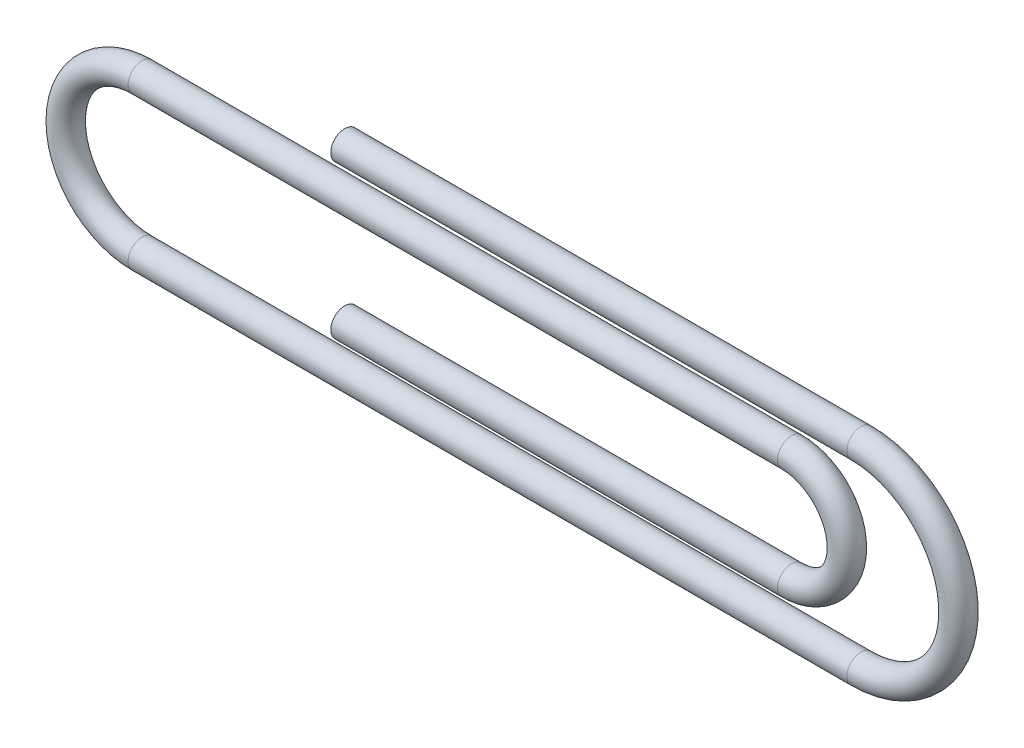
SolidWorks part; units mm, degrees
material "___"
ref_plane "Front Plane" through (0, 0, 0) normal (0, 0, 1) x (1, 0, 0)
ref_plane "Top Plane" through (0, 0, 0) normal (0, 1, 0) x (1, 0, 0)
ref_plane "Right Plane" through (0, 0, 0) normal (1, 0, 0) x (0, 0, -1)
sketch "Sketch1" plane through (0, 0, 0) normal (0, 0, 1) x (1, 0, 0)
  line L0 (0, 0) -> (18.5, 0)
  line L1 (18.5, -7) -> (-7.264, -7)
  line L2 (-7.264, -1.5279) -> (16.014, -1.5279)
  line L3 (16.014, -5.5) -> (0, -5.5)
  line L4 (-10, -4.264) -> (22, -3.5) construction
  arc A0 (18.5, 0) -> (18.5, -7) centre (18.5, -3.5) cw
  arc A1 (-7.264, -7) -> (-7.264, -1.5279) centre (-7.264, -4.264) cw
  arc A2 (16.014, -1.5279) -> (16.014, -5.5) centre (16.014, -3.514) cw
  point P14 (18, -3.514)
  point P15 (0, 0)
  dimension "D3" = 3.5
  dimension "D1" = 32
  dimension "D2" = 4
  dimension "D4" = 10
  dimension "D5" = 1.5
  dimension "D6" = 1.5279
sketch "Sketch2" plane through (0, 0, 0) normal (1, 0, 0) x (0, 0, -1)
  circle A0 centre (0, 0) radius 0.5
  dimension "D1" = 1
sweep "Sweep1" add profiles "Sketch2" path "Sketch1"
